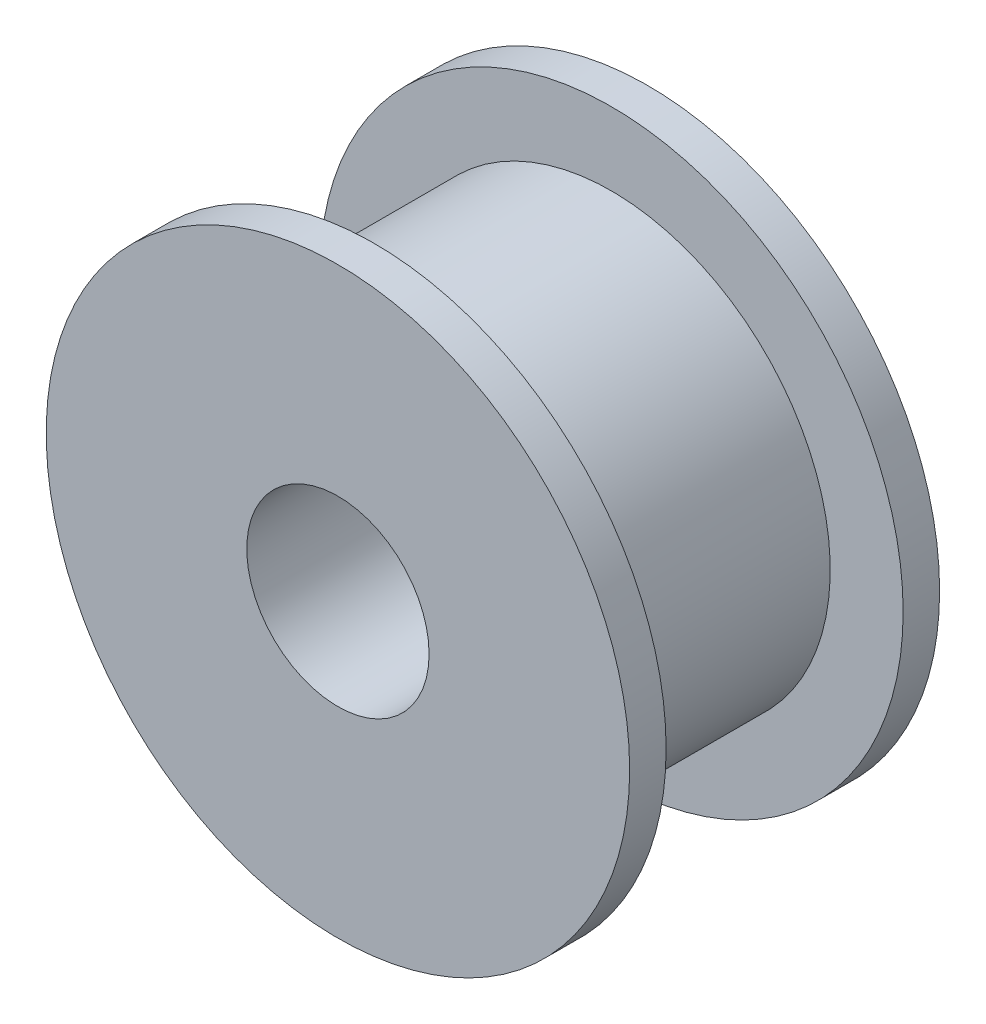
SolidWorks part; units mm, degrees
ref_plane "前视基准面" through (0, 0, 0) normal (0, 0, 1) x (1, 0, 0)
ref_plane "上视基准面" through (0, 0, 0) normal (0, 1, 0) x (1, 0, 0)
ref_plane "右视基准面" through (0, 0, 0) normal (1, 0, 0) x (0, 0, -1)
sketch "草图1" plane through (0, 0, 0) normal (0, 0, 1) x (1, 0, 0)
  circle A0 centre (0, 0) radius 2.5
  circle A1 centre (0, 0) radius 8
  dimension "D1" = 5
  dimension "D2" = 16
extrude "凸台-拉伸1" add sketch "草图1" along normal blind 1
sketch "草图2" plane through (0, 0, 1) normal (0, 0, 1) x (1, 0, 0)
  circle A0 centre (0, 0) radius 2.5 construction
  circle A1 centre (0, 0) radius 2.5
  circle A2 centre (0, 0) radius 6
  dimension "D1" = 12
extrude "凸台-拉伸2" add sketch "草图2" along normal blind 6.5
sketch "草图3" plane through (0, 0, 7.5) normal (0, 0, 1) x (1, 0, 0)
  circle A0 centre (0, 0) radius 6 construction
  circle A1 centre (0, 0) radius 8
  circle A2 centre (0, 0) radius 8
  circle A3 centre (0, 0) radius 6
  dimension "D1" = 0
extrude "凸台-拉伸3" add sketch "草图3" along normal blind 1 separate body
sketch "草图4" plane through (0, 0, 7.5) normal (0, 0, 1) x (1, 0, 0)
  circle A0 centre (0, 0) radius 2.5 construction
  circle A1 centre (0, 0) radius 6
  circle A2 centre (0, 0) radius 6
  circle A3 centre (0, 0) radius 2.5
  dimension "D1" = 0
extrude "凸台-拉伸4" add sketch "草图4" along normal blind 1
